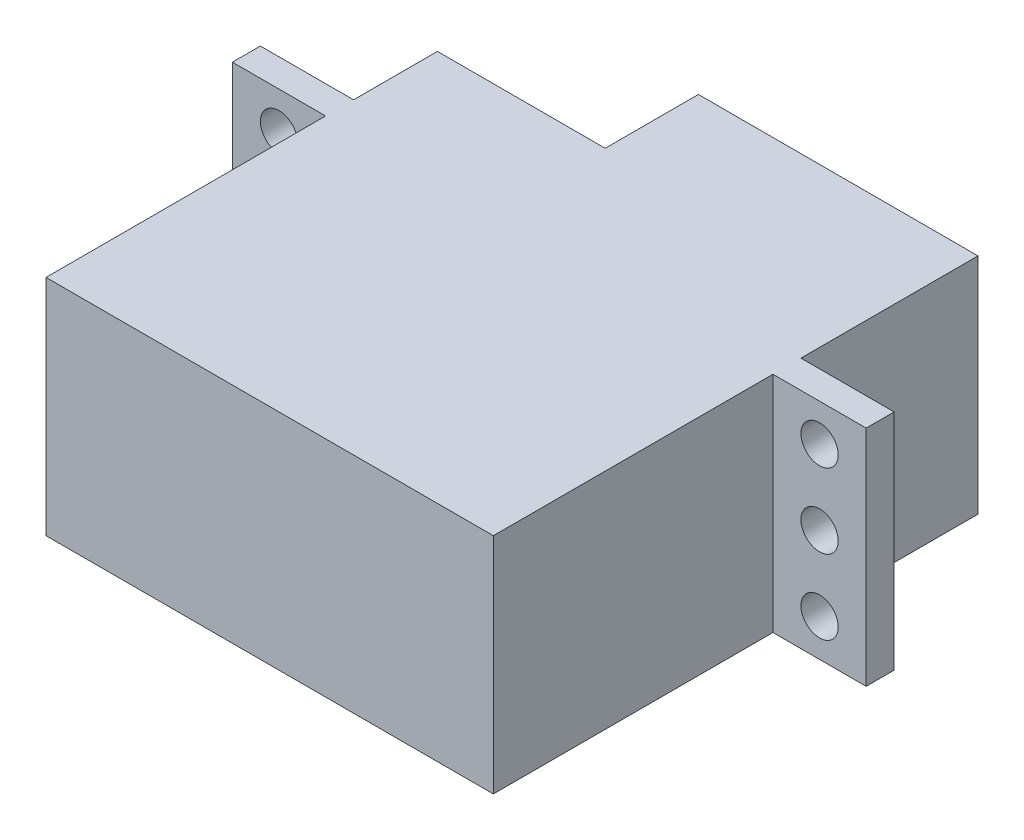
SolidWorks part; units mm, degrees
ref_plane "Front Plane" through (0, 0, 0) normal (0, 0, 1) x (1, 0, 0)
ref_plane "Top Plane" through (0, 0, 0) normal (0, 1, 0) x (1, 0, 0)
ref_plane "Right Plane" through (0, 0, 0) normal (1, 0, 0) x (0, 0, -1)
sketch "Sketch1" plane through (0, 0, 0) normal (0, 0, 1) x (1, 0, 0)
  line L1 (0, 0) -> (24, 0)
  line L2 (0, 0) -> (0, -12)
  line L3 (0, -12) -> (24, -12)
  line L4 (24, 0) -> (24, -12)
  dimension "D1" = 24
  dimension "D2" = 12
extrude "Boss-Extrude1" add sketch "Sketch1" along normal blind 21
ref_plane "Plane1" through (0, 0, 6) normal (0, 0, 1) x (1, 0, 0)
sketch "Sketch2" plane through (0, 0, 6) normal (0, 0, 1) x (1, 0, 0)
  line L0 (0, -12) -> (24, -12) construction
  line L1 (-5, 0) -> (29, 0)
  line L2 (-5, 0) -> (-5, -12)
  line L3 (-5, -12) -> (29, -12)
  line L4 (29, 0) -> (29, -12)
  line L5 (24, 0) -> (0, 0) construction
  line L6 (0, 0) -> (0, -12) construction
  line L7 (24, -12) -> (24, 0) construction
  line L8 (-3.5, -2) -> (-5, -2) construction
  line L9 (-1.5, -2) -> (0, -2) construction
  line L10 (-2.5, -1) -> (-2.5, 0) construction
  line L11 (27.5, -2) -> (29, -2) construction
  circle A0 centre (-2.5, -2) radius 1
  circle A1 centre (26.5, -2) radius 1
  circle A2 centre (26.5, -6) radius 1
  circle A3 centre (26.5, -10) radius 1
  circle A4 centre (-2.5, -6) radius 1
  circle A5 centre (-2.5, -10) radius 1
  dimension "D3" = 2
  dimension "D1" = 5
  dimension "D2" = 5
  dimension "D4" = 1
  dimension "D5" = 2
  dimension "D6" = 3
extrude "Boss-Extrude2" add sketch "Sketch2" against normal blind 1.5
sketch "Sketch3" plane through (0, 0, 0) normal (0, 0, -1) x (-1, 0, 0)
  line L0 (0, -12) -> (-24, -12) construction
  line L1 (-24, 0) -> (-9, 0)
  line L2 (-24, 0) -> (-24, -12)
  line L3 (-24, -12) -> (-9, -12)
  line L4 (-9, 0) -> (-9, -12)
  dimension "D1" = 15
extrude "Boss-Extrude3" add sketch "Sketch3" along normal blind 5
sketch "Sketch4" plane through (0, 0, -5) normal (0, 0, -1) x (-1, 0, 0)
  line L0 (-24, -12) -> (-24, 0) construction
  line L1 (-17, -4) -> (-17, 0) construction
  line L3 (-17, -8) -> (-17, -12) construction
  line L4 (-24, -12) -> (-9, -12) construction
  line L5 (-9, 0) -> (-24, 0) construction
  circle A0 centre (-17, -6) radius 2
  dimension "D1" = 4
  dimension "D2" = 7
extrude "Boss-Extrude4" add sketch "Sketch4" along normal blind 4
